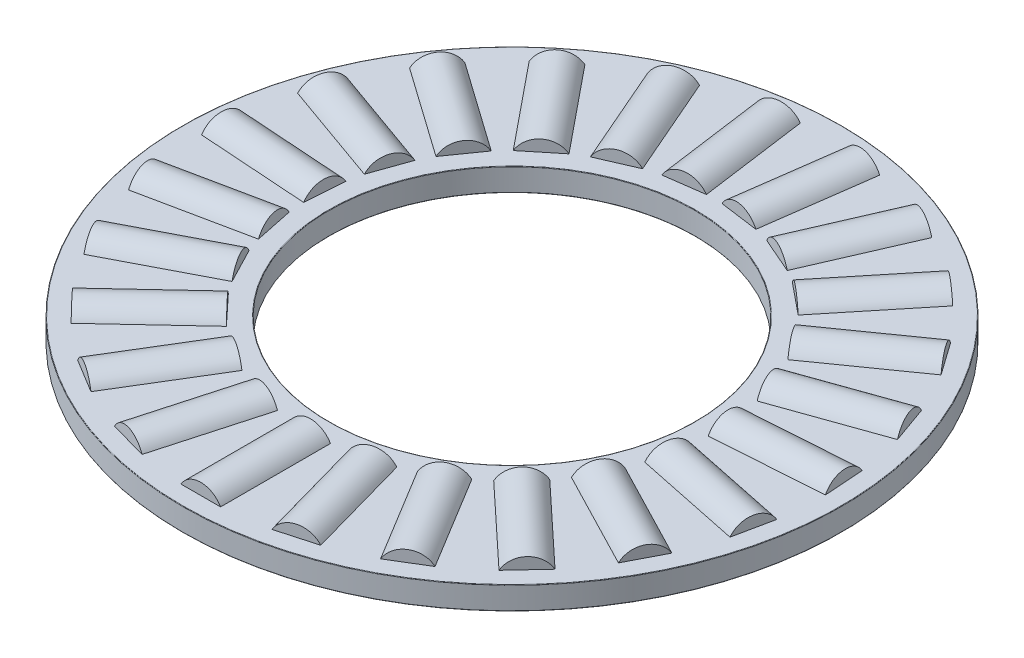
SolidWorks part; units mm, degrees
ref_plane "Front Plane" through (0, 0, 0) normal (0, 0, 1) x (1, 0, 0)
ref_plane "Top Plane" through (0, 0, 0) normal (0, 1, 0) x (1, 0, 0)
ref_plane "Right Plane" through (0, 0, 0) normal (1, 0, 0) x (0, 0, -1)
sketch "Sketch1" plane through (0, 0, 0) normal (1, 0, 0) x (0, 0, -1)
  line L0 (-14.2875, 0) -> (14.2875, 0) construction
  line L1 (0, -0.9922) -> (0, 0.9922) construction
  line L2 (-14.2875, 0.4961) -> (-7.9375, 0.4961)
  line L3 (-14.2875, 0.4961) -> (-14.2875, -0.4961)
  line L4 (-14.2875, -0.4961) -> (-7.9375, -0.4961)
  line L5 (-7.9375, 0.4961) -> (-7.9375, -0.4961)
  line L7 (-11.1125, 0.9922) -> (-11.1125, 0.4961) construction
  line L8 (-13.4938, 0.9922) -> (-8.7312, 0.9922) construction
  line L9 (-13.4938, 0.9922) -> (-13.4938, -0.9922) construction
  line L10 (-13.4938, -0.9922) -> (-8.7312, -0.9922) construction
  line L11 (-8.7312, 0.9922) -> (-8.7312, -0.9922) construction
  point P16 (-13.4938, 0)
  dimension "D1" = 4.7625
  dimension "OD" = 28.575
  dimension "Shaft Dia" = 15.875
  dimension "Th" = 1.9844
  dimension "D2" = 0.9922
  dimension "D3" = 6.35
revolve "Revolve1" add sketch "Sketch1" angle 360 about L1
sketch "Sketch3" plane through (0, 0, 0) normal (1, 0, 0) x (0, 0, -1)
  line L0 (-13.4938, 0.9922) -> (-13.4938, -0.9922) construction
  line L1 (-13.4938, 0) -> (-8.7312, 0)
  line L2 (-13.4938, 0) -> (-13.4938, 0.9922)
  line L3 (-13.4938, 0.9922) -> (-8.7312, 0.9922)
  line L4 (-8.7312, 0) -> (-8.7312, 0.9922)
revolve "Cut-Revolve1" cut sketch "Sketch3" angle 360 about L1
sketch "Sketch2" plane through (0, 0, 0) normal (1, 0, 0) x (0, 0, -1)
  line L1 (-13.4938, 0) -> (-8.7312, 0)
  line L2 (-13.4938, 0) -> (-13.4938, 0.9922)
  line L3 (-13.4938, 0.9922) -> (-8.7312, 0.9922)
  line L4 (-8.7312, 0) -> (-8.7312, 0.9922)
revolve "Revolve2" add sketch "Sketch2" angle 360 about L1
ref_axis "Axis1" through (0, 0.9922, 0) along (0, -1, 0)
pattern_circular "CirPattern1" count 23 every 15.652 about axis through (0, 0.9922, 0) along (0, -1, 0) of bodies 187 411
pattern_circular "CirPattern2" count 23 every 15.652 about axis through (0, 0, 0) along (0, 1, 0) of "Cut-Revolve1"
sketch "Sketch4" plane through (0, 0, 0) normal (1, 0, 0) x (0, 0, -1)
  line L0 (-14.2875, 0.4961) -> (-14.2875, -0.4961) construction
  line L1 (-14.2875, 9.1091) -> (-7.9375, 9.1091)
  line L2 (-14.2875, 9.1091) -> (-14.2875, 9.9219)
  line L3 (-14.2875, 9.9219) -> (-7.9375, 9.9219)
  line L4 (-7.9375, 9.1091) -> (-7.9375, 9.9219)
  line L5 (-14.2875, -9.9219) -> (-7.9375, -9.9219)
  line L6 (-14.2875, -9.9219) -> (-14.2875, -9.1091)
  line L7 (-14.2875, -9.1091) -> (-7.9375, -9.1091)
  line L8 (-7.9375, -9.9219) -> (-7.9375, -9.1091)
  line L10 (-7.9375, 0.4961) -> (-7.9375, -0.4961) construction
  line L11 (0, 0) -> (-14.2875, 0) construction
  line L12 (-14.2875, 0) -> (14.2875, 0) construction
  line L13 (0, -0.9922) -> (0, 0.9922) construction
  dimension "Ht" = 19.8438
  dimension "Washer Th" = 0.8128
  dimension "Washer ID" = 15.875
  dimension "Washer OD" = 28.575
revolve "Revolve3" [suppressed] add sketch "Sketch4" angle 360 about L1
fillet "Fillet1" [suppressed] radius 0.0198
fillet "Fillet2" radius 0.0198 4 edges at (0, -0.4961, -7.9375) (0, 0.4961, -7.9375) (0, -0.4961, -14.2875) (0, 0.4961, -14.2875)
fillet "Fillet3" [suppressed] radius 0.0198
equation "\"D2@Sketch1\" = \"Th@Sketch1\"*.5"
equation "\"D1@Fillet1\" = \"Th@Sketch1\"*.01"
equation "\"D1@Fillet2\" = \"D1@Fillet1\""
equation "\"D1@Fillet3\" = \"D1@Fillet1\""
equation "\"D1@Sketch1\" = \"D3@Sketch1\"*.75"
equation "\"Angle@CirPattern1\" = 360/\"Rollers@CirPattern1\""
equation "\"Rollers@CirPattern1\" = \"OD@Sketch1\"*20"
equation "\"D1@CirPattern2\" = \"Rollers@CirPattern1\""
equation "\"D2@CirPattern2\" = \"Angle@CirPattern1\""
equation "\"Ht@Sketch4\" = \"Th@Sketch1\"*10"
